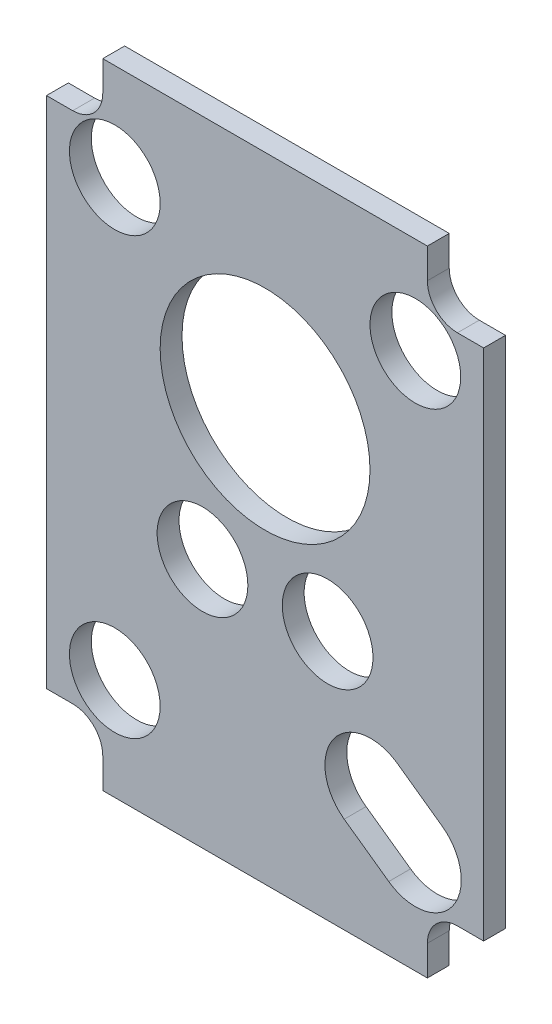
SolidWorks part; units mm, degrees
ref_plane "Front Plane" through (0, 0, 0) normal (0, 0, 1) x (1, 0, 0)
ref_plane "Top Plane" through (0, 0, 0) normal (0, 1, 0) x (1, 0, 0)
ref_plane "Right Plane" through (0, 0, 0) normal (1, 0, 0) x (0, 0, -1)
sketch "Sketch1" plane through (0, 0, 0) normal (0, 0, 1) x (1, 0, 0)
  line L0 (13.75, -19.7) -> (9.6769, -16.8) construction
  line L3 (-14.85, 26.25) -> (-14.85, 29)
  line L8 (17, -29) -> (-17, -29)
  line L9 (20, -26) -> (20, 26)
  line L10 (-17.6, 23.5) -> (-20, 23.5)
  line L11 (17, 29) -> (-17, 29)
  line L14 (-20, -26) -> (-20, 26)
  line L15 (20, -29) -> (-20, 29) construction
  line L16 (20, 29) -> (-20, -29) construction
  line L17 (11.314, -23.1214) -> (7.2409, -20.2214)
  line L18 (16.186, -16.2786) -> (12.1129, -13.3786)
  line L19 (0, -29) -> (0, 29) construction
  line L20 (14.85, 26.25) -> (14.85, 29)
  line L21 (17.6, 23.5) -> (20, 23.5)
  line L22 (17.6, -23.5) -> (20, -23.5)
  line L23 (14.85, -26.25) -> (14.85, -29)
  line L24 (-14.85, -26.25) -> (-14.85, -29)
  line L25 (-17.6, -23.5) -> (-20, -23.5)
  arc A14 (-17, -29) -> (-20, -26) centre (-17, -26) cw
  arc A15 (17, -29) -> (20, -26) centre (17, -26) ccw
  arc A16 (20, 26) -> (17, 29) centre (17, 26) ccw
  arc A17 (-17, 29) -> (-20, 26) centre (-17, 26) ccw
  circle A18 centre (-13.75, 20.15) radius 4.15
  circle A19 centre (13.75, 20.15) radius 4.15
  circle A20 centre (-13.75, -19.7) radius 4.15
  arc A21 (11.314, -23.1214) -> (16.186, -16.2786) centre (13.75, -19.7) ccw
  arc A22 (12.1129, -13.3786) -> (7.2409, -20.2214) centre (9.6769, -16.8) ccw
  circle A23 centre (0, 8.65) radius 9.6
  circle A24 centre (-5.725, -6.1) radius 4.15
  circle A25 centre (5.725, -6.1) radius 4.15
  circle A26 centre (-17.6, -26.25) radius 2.75
  circle A27 centre (17.6, -26.25) radius 2.75
  circle A28 centre (-17.6, 26.25) radius 2.75
  circle A29 centre (17.6, 26.25) radius 2.75
  point P0 (0, 0)
  point P14 (6.2555, -14.364)
  point P31 (11.7135, -18.25)
  point P37 (5.725, -10.25)
  dimension "D1" = 58
  dimension "D2" = 40
  dimension "D3" = 3
  dimension "D4" = 8.4
  dimension "D5" = 8.3
  dimension "D6" = 19.2
  dimension "D16" = 5.5
  dimension "D7" = 9.3
  dimension "D8" = 27.5
  dimension "D9" = 39.85
  dimension "D10" = 5
  dimension "D11" = 12.2
  dimension "D12" = 20.35
  dimension "D13" = 11.45
  dimension "D14" = 22.9
  dimension "D15" = 35.2
extrude "Boss-Extrude1" add sketch "Sketch1" along normal blind 2 contours A29 A16 L11 A17 A28 L14 A26 A14 L8 A15 A27 L9 A25 A24 A23 A22 L18 A21 L17 A20 A19 A18
